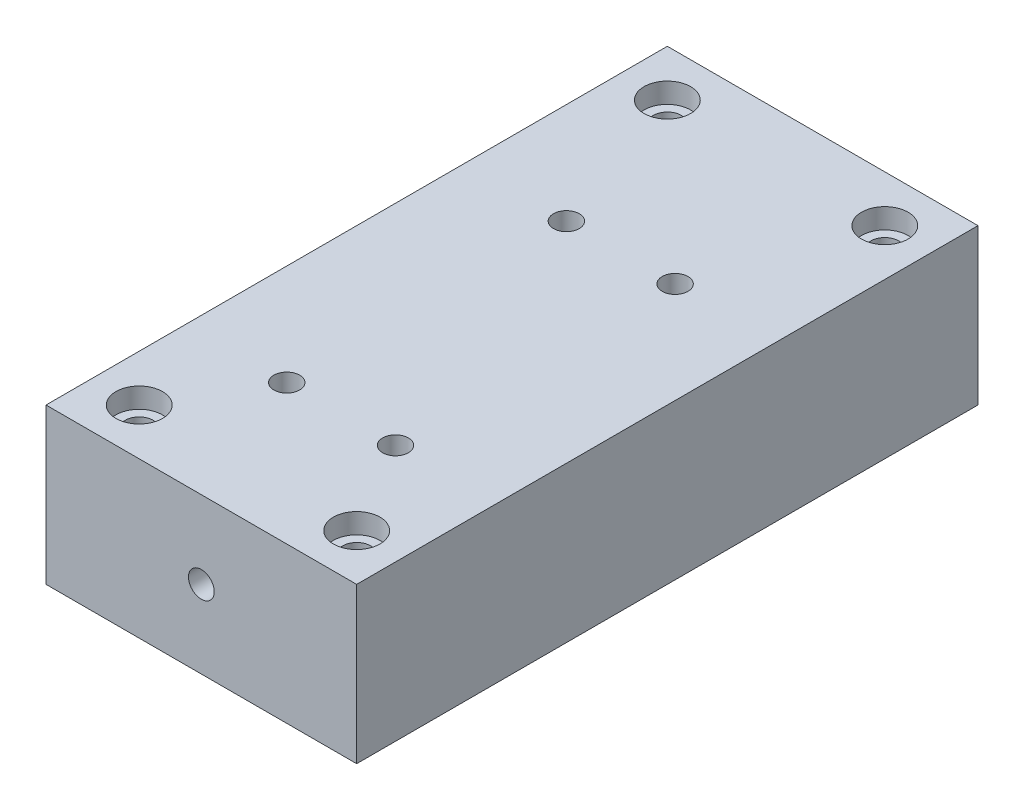
SolidWorks part; units mm, degrees
ref_plane "Ebene vorne" through (0, 0, 0) normal (0, 0, 1) x (1, 0, 0)
ref_plane "Ebene oben" through (0, 0, 0) normal (0, 1, 0) x (1, 0, 0)
ref_plane "Ebene rechts" through (0, 0, 0) normal (1, 0, 0) x (0, 0, -1)
sketch "Skizze1" plane through (0, 0, 0) normal (0, 0, 1) x (1, 0, 0)
  line L1 (50, -25) -> (-50, -25)
  line L2 (50, -25) -> (50, 25)
  line L3 (50, 25) -> (-50, 25)
  line L4 (-50, -25) -> (-50, 25)
  line L5 (50, -25) -> (-50, 25) construction
  line L6 (50, 25) -> (-50, -25) construction
  point P0 (0, 0)
  dimension "D1" = 50
  dimension "D2" = 100
extrude "Aufsatz-Linear austragen1" add sketch "Skizze1" along normal blind 200 contours L4 L3 L2 L1
ref_plane "Ebene1" through (0, 0, 100) normal (0, 0, 1) x (1, 0, 0)
sketch "Skizze3" plane through (0, 25, 0) normal (0, 1, 0) x (1, 0, 0)
  line L0 (-50, -200) -> (-50, 0) construction
  line L1 (50, -200) -> (50, 0) construction
  line L2 (-27.5, -100) -> (27.5, -100) construction
  circle A0 centre (0, -150) radius 50
  dimension "D1" = 50
hole_wizard "Stirnsenkung für M8 Senkschraube (Kopf Button)4" positions "Skizze9" profile "Skizze10" counterbore size "M8" standard "ANSI Metrisch" end condition through all
sketch "Skizze9" plane through (0, 25, 0) normal (0, 1, 0) x (1, 0, 0)
  line L1 (50, -200) -> (-50, -200) construction
  line L2 (-50, -200) -> (-50, 0) construction
  circle A0 centre (-35, -185) radius 15
  point P1 (-35, -185)
  dimension "D1" = 30
sketch "Skizze10" plane through (-35, 25, 185) normal (1, 0, 0) x (0, 0, 1)
  line L0 (0, 0) -> (0, 50)
  line L1 (0, 50) -> (4.5, 50)
  line L3 (4.5, 50) -> (4.5, 6.5)
  line L4 (4.5, 6.5) -> (7.5, 6.5)
  line L5 (7.5, 6.5) -> (7.5, 0)
  line L7 (7.5, 0) -> (0, 0)
  line L11 (0, -6.35) -> (0, 107.95) construction
  dimension "Bohrerdurchmesser" = 9
  dimension "Bohrungstiefe" = 50
  dimension "Senkdurchmesser2" = 15
  dimension "Senktiefe2" = 6.5
mirror "Spiegeln2" about plane through (0, 0, 0) normal (1, 0, 0) of "Stirnsenkung für M8 Senkschraube (Kopf Button)4"
mirror "Spiegeln3" about plane through (0, 0, 100) normal (0, 0, 1) of "Spiegeln2", "Stirnsenkung für M8 Senkschraube (Kopf Button)4"
hole_wizard "Kernloch für M8 Helicoil0" positions "Skizze12" profile "Skizze13" hole size "M8x1.25" standard "ANSI Metrisch"
sketch "Skizze12" plane through (-50, 0, 0) normal (-1, 0, 0) x (0, 0, 1)
  point P0 (35, -7.5)
sketch "Skizze13" plane through (-50, -7.5, 35) normal (0, 1, 0) x (0, 0, 1)
  line L0 (0, 0) -> (0, 22.4936)
  line L1 (0, 22.4936) -> (4.15, 20)
  line L2 (4.15, 20) -> (4.15, 0)
  line L5 (4.15, 0) -> (0, 0)
  line L10 (0, 22.4936) -> (-4.15, 20) construction
  line L11 (0, -6.35) -> (0, 107.95) construction
  dimension "Bohrerdurchmesser" = 8.3
  dimension "Bohrungstiefe" = 20
  dimension "Spitzenwinkel" = 118
hole_wizard "Kernloch für M8 Helicoil0" positions "Skizze15" profile "Skizze14" hole size "M8x1.25" standard "ANSI Metrisch"
sketch "Skizze15" plane through (-50, 0, 0) normal (-1, 0, 0) x (0, 0, 1)
  point P0 (165, -7.5)
sketch "Skizze14" plane through (-50, -7.5, 165) normal (0, 1, 0) x (0, 0, 1)
  line L0 (0, 0) -> (0, 22.4936)
  line L1 (0, 22.4936) -> (4.15, 20)
  line L2 (4.15, 20) -> (4.15, 0)
  line L5 (4.15, 0) -> (0, 0)
  line L10 (0, 22.4936) -> (-4.15, 20) construction
  line L11 (0, -6.35) -> (0, 107.95) construction
  dimension "Bohrerdurchmesser" = 8.3
  dimension "Bohrungstiefe" = 20
  dimension "Spitzenwinkel" = 118
hole_wizard "Kernloch für M8 Helicoil3" positions "Skizze24" profile "Skizze23" hole size "M8x1.25" standard "ANSI Metrisch"
sketch "Skizze24" plane through (0, 0, 200) normal (0, 0, 1) x (1, 0, 0)
  point P0 (0, 0)
sketch "Skizze23" plane through (0, 0, 200) normal (1, 0, 0) x (0, -1, 0)
  line L0 (0, 0) -> (0, 22.4936)
  line L1 (0, 22.4936) -> (4.15, 20)
  line L2 (4.15, 20) -> (4.15, 0)
  line L5 (4.15, 0) -> (0, 0)
  line L10 (0, 22.4936) -> (-4.15, 20) construction
  line L11 (0, -6.35) -> (0, 107.95) construction
  dimension "Bohrerdurchmesser" = 8.3
  dimension "Bohrungstiefe" = 20
  dimension "Spitzenwinkel" = 118
hole_wizard "Kernloch für M8 Helicoil4" positions "Skizze26" profile "Skizze25" hole size "M8x1.25" standard "ANSI Metrisch"
sketch "Skizze26" plane through (0, 25, 0) normal (0, 1, 0) x (1, 0, 0)
  point P0 (-17.5, -65)
  point P3 (17.5, -65)
  point P6 (17.5, -155)
  point P9 (-17.5, -155)
sketch "Skizze25" plane through (-17.5, 25, 65) normal (1, 0, 0) x (0, 0, 1)
  line L0 (0, 0) -> (0, 22.4936)
  line L1 (0, 22.4936) -> (4.15, 20)
  line L2 (4.15, 20) -> (4.15, 0)
  line L5 (4.15, 0) -> (0, 0)
  line L10 (0, 22.4936) -> (-4.15, 20) construction
  line L11 (0, -6.35) -> (0, 107.95) construction
  dimension "Bohrerdurchmesser" = 8.3
  dimension "Bohrungstiefe" = 20
  dimension "Spitzenwinkel" = 118
hole_wizard "Kernloch für M8 Helicoil1" positions "Skizze19" profile "Skizze18" hole size "M8x1.25" standard "ANSI Metrisch"
sketch "Skizze19" plane through (0, 0, 0) normal (0, 0, -1) x (-1, 0, 0)
  point P0 (17.5347, 5)
sketch "Skizze18" plane through (-17.5347, 5, 0) normal (1, 0, 0) x (0, 1, 0)
  line L0 (0, 0) -> (0, 22.4936)
  line L1 (0, 22.4936) -> (4.15, 20)
  line L2 (4.15, 20) -> (4.15, 0)
  line L5 (4.15, 0) -> (0, 0)
  line L10 (0, 22.4936) -> (-4.15, 20) construction
  line L11 (0, -6.35) -> (0, 107.95) construction
  dimension "Bohrerdurchmesser" = 8.3
  dimension "Bohrungstiefe" = 20
  dimension "Spitzenwinkel" = 118
hole_wizard "Kernloch für M8 Helicoil2" positions "Skizze21" profile "Skizze22" hole size "M8x1.25" standard "ANSI Metrisch"
sketch "Skizze21" plane through (0, 0, 200) normal (0, 0, 1) x (1, 0, 0)
  point P0 (0, 0)
sketch "Skizze22" plane through (0, 0, 200) normal (1, 0, 0) x (0, -1, 0)
  line L0 (0, 0) -> (0, 22.4936)
  line L1 (0, 22.4936) -> (4.15, 20)
  line L2 (4.15, 20) -> (4.15, 0)
  line L5 (4.15, 0) -> (0, 0)
  line L10 (0, 22.4936) -> (-4.15, 20) construction
  line L11 (0, -6.35) -> (0, 107.95) construction
  dimension "Bohrerdurchmesser" = 8.3
  dimension "Bohrungstiefe" = 20
  dimension "Spitzenwinkel" = 118
